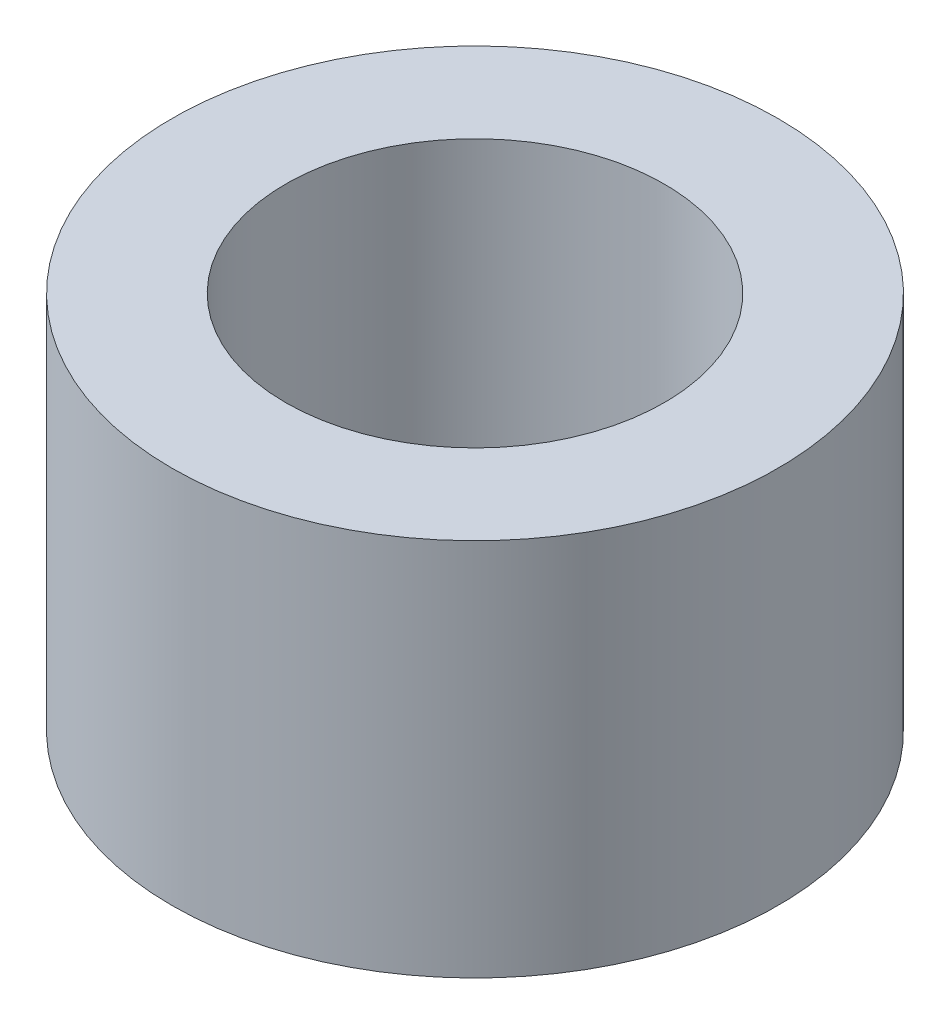
SolidWorks part; units mm, degrees
ref_plane "Front Plane" through (0, 0, 0) normal (0, 0, 1) x (1, 0, 0)
ref_plane "Top Plane" through (0, 0, 0) normal (0, 1, 0) x (1, 0, 0)
ref_plane "Right Plane" through (0, 0, 0) normal (1, 0, 0) x (0, 0, -1)
sketch "Sketch1" plane through (0, 0, 0) normal (0, 1, 0) x (1, 0, 0)
  circle A0 centre (0, 0) radius 3.175
  circle A1 centre (0, 0) radius 5.08
  dimension "D1" = 6.35
  dimension "D2" = 1.905
extrude "Boss-Extrude1" add sketch "Sketch1" along normal blind 6.35
